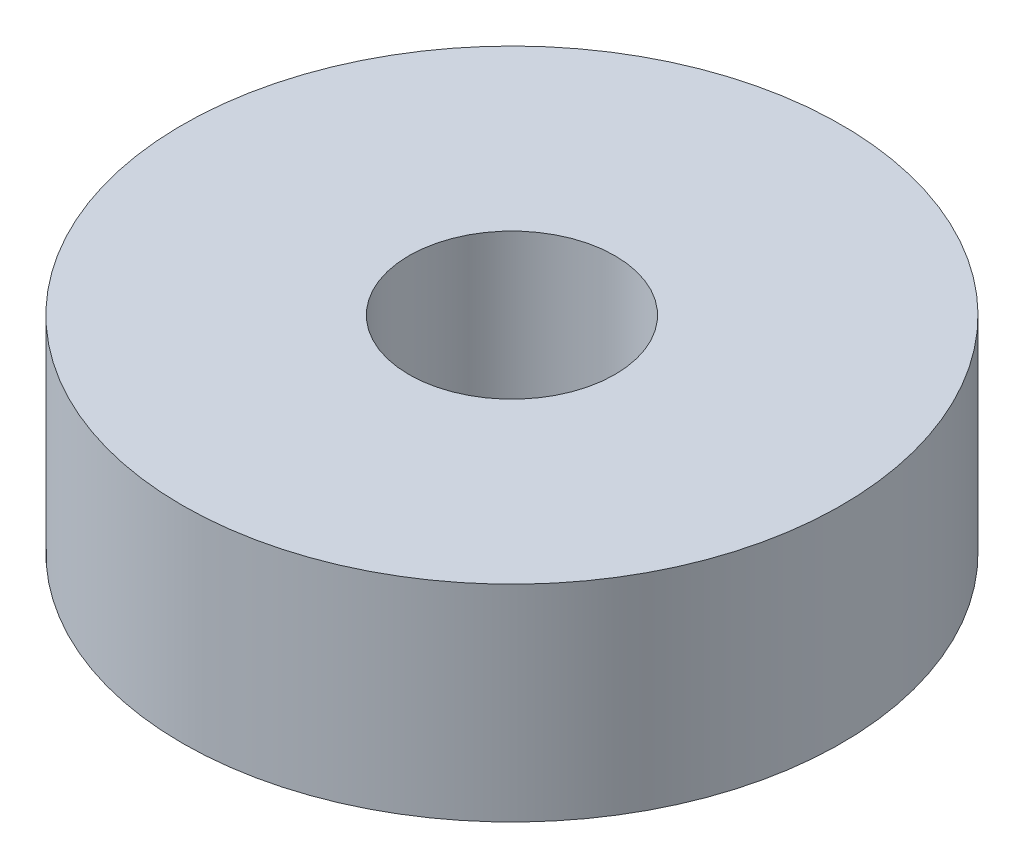
SolidWorks part; units mm, degrees
material "Литая легированная сталь"
ref_plane "Спереди" through (0, 0, 0) normal (0, 0, 1) x (1, 0, 0)
ref_plane "Сверху" through (0, 0, 0) normal (0, 1, 0) x (1, 0, 0)
ref_plane "Справа" through (0, 0, 0) normal (1, 0, 0) x (0, 0, -1)
sketch "Эскиз1" plane through (0, 0, 0) normal (0, 1, 0) x (1, 0, 0)
  circle A0 centre (0, 0) radius 8
  circle A1 centre (0, 0) radius 2.5
  dimension "D1" = 16
  dimension "D2" = 5
extrude "Бобышка-Вытянуть1" add sketch "Эскиз1" along normal blind 5
